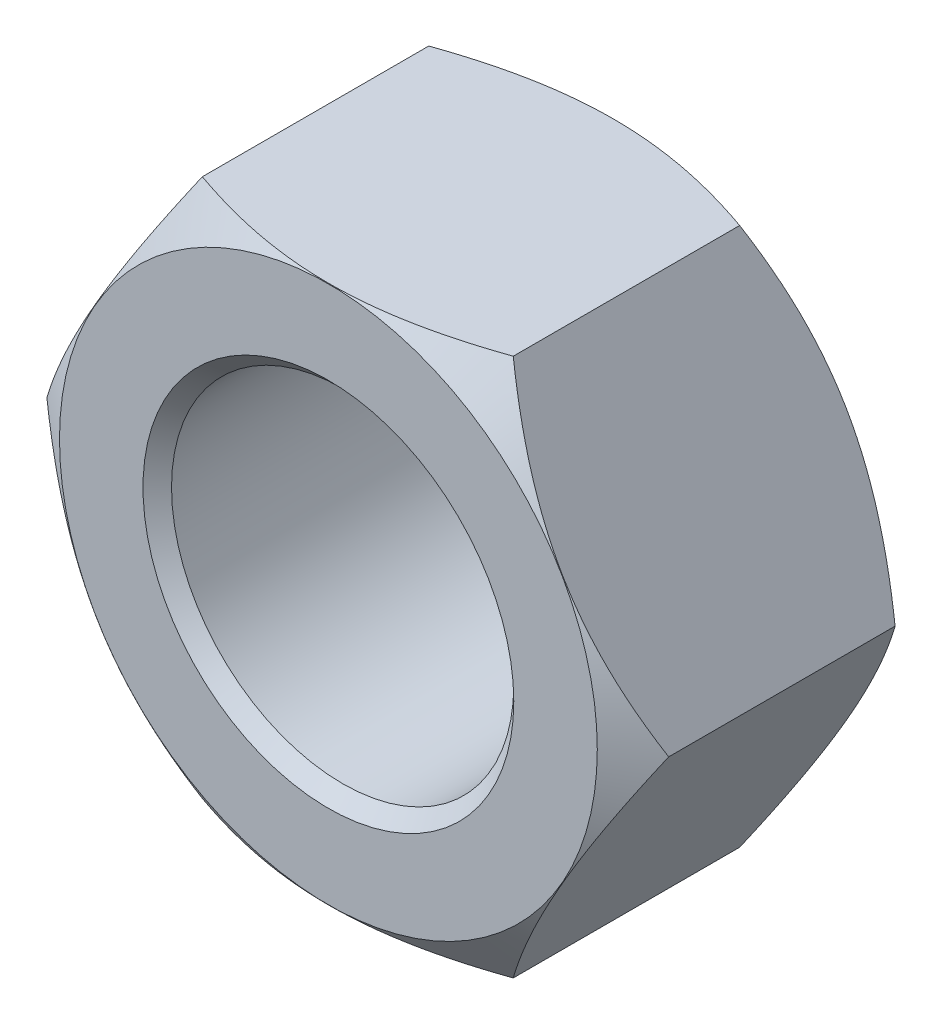
SolidWorks part; units mm, degrees
material "Plain Carbon Steel"
ref_plane "Спереди" through (0, 0, 0) normal (0, 0, 1) x (1, 0, 0)
ref_plane "Сверху" through (0, 0, 0) normal (0, 1, 0) x (1, 0, 0)
ref_plane "Справа" through (0, 0, 0) normal (1, 0, 0) x (0, 0, -1)
sketch "Sketch1" plane through (0, 0, 0) normal (0, 0, 1) x (1, 0, 0)
  line L1 (5.45, 0) -> (2.725, 4.7198)
  line L2 (2.725, 4.7198) -> (-2.725, 4.7198)
  line L3 (-2.725, 4.7198) -> (-5.45, 0)
  line L4 (-5.45, 0) -> (-2.725, -4.7198)
  line L5 (-2.725, -4.7198) -> (2.725, -4.7198)
  line L6 (2.725, -4.7198) -> (5.45, 0)
  circle A0 centre (0, 0) radius 4.7198 construction
  circle A1 centre (0, 0) radius 3
  dimension "D1" = 6
  dimension "D2" = 10.9
extrude "Boss-Extrude1" add sketch "Sketch1" along normal blind 5
chamfer "Chamfer1" distance 0.25 angle 45 2 edges at (3, 0, 0) (3, 0, 5)
sketch "Sketch2" plane through (0, 0, 0) normal (0, 1, 0) x (1, 0, 0)
  line L0 (0, -5.5) -> (0, 0.5) construction
  line L1 (-1, -5.5) -> (-4, -5.5)
  line L2 (-4, -5.5) -> (-6.1422, -4)
  line L3 (-6.1422, -4) -> (-6.1422, -1)
  line L4 (-6.1422, -1) -> (-4, 0.5)
  line L5 (-4, 0.5) -> (-1, 0.5)
  line L6 (-1, 0.5) -> (-1, 1.9802)
  line L7 (-1, 1.9802) -> (-7.7509, 1.9802)
  line L8 (-7.7509, 1.9802) -> (-7.7509, -6.984)
  line L9 (-7.7509, -6.984) -> (-1, -6.984)
  line L10 (-1, -6.984) -> (-1, -5.5)
  line L12 (-3.25, -5) -> (3.25, -5) construction
  line L13 (3.25, 0) -> (-3.25, 0) construction
  dimension "D1" = 1
  dimension "D2" = 35
  dimension "D3" = 35
  dimension "D4" = 0.5
  dimension "D5" = 0.5
  dimension "D6" = 3
  dimension "D7" = 3
revolve "Cut-Revolve1" cut sketch "Sketch2" angle 360 about L0
